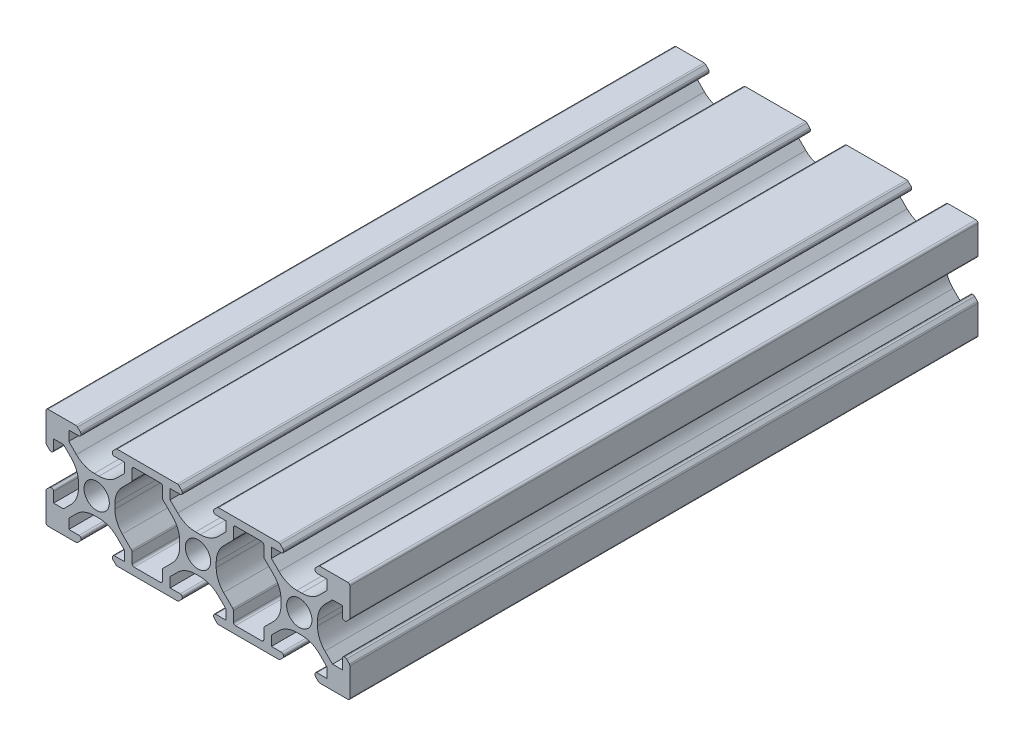
SolidWorks part; units mm, degrees
material "6063-O"
ref_plane "Plano frontal" through (0, 0, 0) normal (0, 0, 1) x (1, 0, 0)
ref_plane "Plano superior" through (0, 0, 0) normal (0, 1, 0) x (1, 0, 0)
ref_plane "Plano direito" through (0, 0, 0) normal (1, 0, 0) x (0, 0, -1)
sketch "Esboço1" plane through (0, 0, 0) normal (0, 0, 1) x (1, 0, 0)
  line L0 (-9.0343, 3.1) -> (-8.9, 3.1)
  line L3 (-10, 10) -> (-4.0657, 10)
  line L5 (-10, -10) -> (10, 10) construction
  line L6 (-10, 10) -> (10, -10) construction
  line L7 (-8.5, 3.5) -> (-8.5, 5.5)
  line L8 (-10, 0) -> (10, 0) construction
  line L9 (0, 10) -> (0, -10) construction
  line L12 (-8.5, 5.5) -> (-6.5607, 5.5)
  line L15 (-6.5607, 5.5) -> (-5.0645, 4.0038)
  line L16 (-3.6, 0.4683) -> (-3.6, 0)
  line L17 (-0.4683, 3.6) -> (0, 3.6)
  line L18 (-5.5, 6.5607) -> (-4.0038, 5.0645)
  line L21 (-5.5, 8.5) -> (-5.5, 6.5607)
  line L24 (-3.5, 8.5) -> (-5.5, 8.5)
  line L25 (-3.1, 9.0343) -> (-3.1, 8.9)
  line L44 (-10, 4.0657) -> (-10, 10)
  line L45 (-9.8828, 3.7828) -> (-9.3172, 3.2172)
  line L46 (-3.7828, 9.8828) -> (-3.2172, 9.3172)
  line L47 (-3.6, 0) -> (-2.5, 0)
  line L48 (0, 3.6) -> (0, 2.5)
  arc A0 (-3.5, 8.5) -> (-3.1, 8.9) centre (-3.5, 8.9) ccw
  arc A1 (-3.7828, 9.8828) -> (-4.0657, 10) centre (-4.0657, 9.6) ccw
  arc A2 (-10, 4.0657) -> (-9.8828, 3.7828) centre (-9.6, 4.0657) ccw
  arc A3 (-8.5, 3.5) -> (-8.9, 3.1) centre (-8.9, 3.5) cw
  arc A4 (-3.2172, 9.3172) -> (-3.1, 9.0343) centre (-3.5, 9.0343) cw
  arc A5 (-9.3172, 3.2172) -> (-9.0343, 3.1) centre (-9.0343, 3.5) ccw
  arc A6 (-3.6, 0.4683) -> (-5.0645, 4.0038) centre (-8.6, 0.4683) ccw
  arc A7 (-4.0038, 5.0645) -> (-0.4683, 3.6) centre (-0.4683, 8.6) ccw
  circle A8 centre (0, 0) radius 2.5
  point P6 (-10, 3.1)
  point P28 (-3.1, 8.5)
  point P31 (-3.1, 10)
  point P33 (-3.9, 10)
  point P36 (-10, 3.9)
  point P39 (-8.5, 3.1)
  point P42 (-3.1, 9.2)
  point P45 (-9.2, 3.1)
  point P48 (-3.6, 2.5393)
  point P51 (-2.5393, 3.6)
  dimension "D5" = 10
  dimension "D9" = 0.4
  dimension "D10" = 0.4
  dimension "D11" = 5
  dimension "D12" = 5
  dimension "D13" = 5
  dimension "D1" = 6.9
  dimension "D2" = 1.5
  dimension "D3" = 3.6
  dimension "D4" = 1.5
  dimension "D6" = 2.4
  dimension "D7" = 3.6
  dimension "D8" = 45
extrude "Ressalto-extrusão1" add sketch "Esboço1" along normal blind 124
sketch "Esboço3" plane through (0, 0, 0) normal (1, 0, 0) x (0, 0, -1)
  line L0 (0, 0) -> (-1000, 0) construction
  dimension "D1" = 1000
pattern_circular "PadrãoCircular1" count 4 over 360 about axis through (0, 0, 0) along (0, 0, 1) of "Ressalto-extrusão1"
pattern_linear "Padrão linear1" count 3 spacing 20 along (1, 0, 0) of "Ressalto-extrusão1", "PadrãoCircular1"
sketch "Esboço4" plane through (0, 0, 0) normal (0, 0, -1) x (-1, 0, 0)
  line L0 (-13.4393, 5.5) -> (-13, 5.9393)
  line L1 (-13, 8.5) -> (-13, 5.9393)
  line L2 (-10, 10) -> (-10, -10) construction
  line L3 (-4.0657, 10) -> (-15.9343, 10) construction
  line L4 (-15.9343, -10) -> (-4.0657, -10) construction
  line L5 (-11.5, 5.5) -> (-13.4393, 5.5) construction
  line L6 (-14.5, 8.5) -> (-14.5, 6.5607) construction
  line L7 (-7, 8.5) -> (-7, 5.9393)
  line L8 (-6.5607, 5.5) -> (-7, 5.9393)
  line L9 (-13, 8.5) -> (-7, 8.5)
  line L10 (-20, 0) -> (0, 0) construction
  line L11 (-13, -8.5) -> (-7, -8.5)
  line L12 (-6.5607, -5.5) -> (-7, -5.9393)
  line L13 (-7, -8.5) -> (-7, -5.9393)
  line L14 (-13, -8.5) -> (-13, -5.9393)
  line L15 (-13.4393, -5.5) -> (-13, -5.9393)
  line L16 (-13.4393, 5.5) -> (-13.4393, -5.5)
  line L17 (-6.5607, -5.5) -> (-6.5607, 5.5)
  line L31 (-40, 0) -> (-20, 0) construction
  line L32 (-33.4393, 5.5) -> (-33, 5.9393) [skipped]
  line L33 (-33, 8.5) -> (-33, 5.9393) [skipped]
  line L34 (-27, 8.5) -> (-27, 5.9393) [skipped]
  line L35 (-26.5607, 5.5) -> (-27, 5.9393) [skipped]
  line L36 (-33, 8.5) -> (-27, 8.5) [skipped]
  line L37 (-33, -8.5) -> (-27, -8.5) [skipped]
  line L38 (-26.5607, -5.5) -> (-27, -5.9393) [skipped]
  line L39 (-27, -8.5) -> (-27, -5.9393) [skipped]
  line L40 (-33, -8.5) -> (-33, -5.9393) [skipped]
  line L41 (-33.4393, -5.5) -> (-33, -5.9393) [skipped]
  line L42 (-33.4393, 5.5) -> (-33.4393, -5.5) [skipped]
  line L43 (-26.5607, -5.5) -> (-26.5607, 5.5) [skipped]
  line L44 (-30, 10) -> (-30, -10) construction
  dimension "D1" = 45
  dimension "D2" = 1.5
  dimension "D3" = 1.5
  dimension "D4" = 2
extrude "Corte-extrusão1" cut sketch "Esboço4" against normal through all
pattern_linear "Padrão linear2" count 2 spacing 20 along (1, 0, 0) of "Corte-extrusão1"
fillet "Filete1" radius 0.4 16 edges at (13, -5.9393, 62) (13, -8.5, 62) (7, -8.5, 62) (7, -5.9393, 62) (7, 8.5, 62) (7, 5.9393, 62) (13, 8.5, 62) (13, 5.9393, 62) (27, -8.5, 62) (27, -5.9393, 62) (27, 8.5, 62) (27, 5.9393, 62) (33, 8.5, 62) (33, -8.5, 62) (33, -5.9393, 62) (33, 5.9393, 62)
fillet "Filete2" radius 0.4 4 edges at (-10, 10, 62) (50, -10, 62) (50, 10, 62) (-10, -10, 62)
ref_plane "Plane1" through (0, 0, 0) normal (0, 1, 0) x (1, 0, 0)
ref_plane "Plane2" through (20, 0, 0) normal (1, 0, 0) x (0, 0, -1)
ref_plane "Plane3" through (0, 0, 62) normal (0, 0, -1) x (-1, 0, 0)
